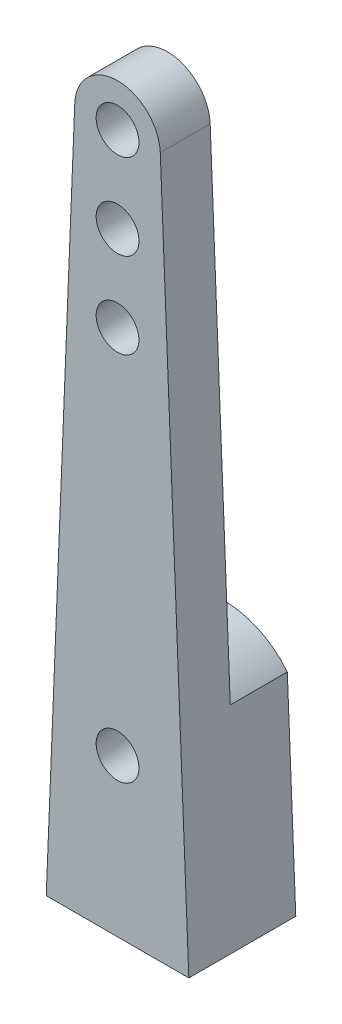
SolidWorks part; units mm, degrees
ref_plane "前视基准面" through (0, 0, 0) normal (0, 0, 1) x (1, 0, 0)
ref_plane "上视基准面" through (0, 0, 0) normal (0, 1, 0) x (1, 0, 0)
ref_plane "右视基准面" through (0, 0, 0) normal (1, 0, 0) x (0, 0, -1)
sketch "草图1" plane through (0, 0, 0) normal (0, 0, 1) x (1, 0, 0)
  line L0 (-5, 0) -> (5, 0)
  line L1 (-2.9975, 49.1222) -> (-5, 0)
  line L2 (0, 23.7926) -> (0, -9.9245) construction
  line L3 (2.9975, 49.1222) -> (5, 0)
  arc A0 (2.9975, 49.1222) -> (-2.9975, 49.1222) centre (0, 49) ccw
  circle A1 centre (0, 49) radius 1.5
  circle A2 centre (0, 43) radius 1.5
  circle A3 centre (0, 37) radius 1.5
  circle A4 centre (0, 11) radius 2.75
  point P1 (0, 52)
  point P9 (0, 0)
  dimension "D1" = 10
  dimension "D2" = 3
  dimension "D4" = 3
  dimension "D5" = 5.5
  dimension "D6" = 38
  dimension "D7" = 32
  dimension "D8" = 26
  dimension "D9" = 3
  dimension "D10" = 3
  dimension "D3" = 52
extrude "凸台-拉伸1" add sketch "草图1" along normal blind 3.5
sketch "草图2" plane through (0, 0, 0) normal (0, 0, -1) x (-1, 0, 0)
  line L3 (5, 0) -> (2.9975, 49.1222)
  line L4 (-2.9975, 49.1222) -> (-5, 0)
  line L5 (-5, 0) -> (5, 0)
  line L6 (5, 0) -> (4.4072, 14.541)
  line L7 (-4.4072, 14.541) -> (-5, 0)
  line L8 (-5, 0) -> (5, 0)
  arc A0 (4.4072, 14.541) -> (-4.4072, 14.541) centre (0, 11) ccw
  arc A1 (2.9975, 49.1222) -> (-2.9975, 49.1222) centre (0, 49) ccw
  dimension "D1" = 0
extrude "凸台-拉伸2" add sketch "草图2" along normal blind 4
sketch "草图4" plane through (0, 0, 3.5) normal (0, 0, 1) x (1, 0, 0)
  circle A1 centre (0, 11) radius 2.75
  circle A2 centre (0, 11) radius 2.75
  dimension "D1" = 0
extrude "凸台-拉伸3" add sketch "草图4" against normal blind 5
sketch "草图5" plane through (0, 0, -4) normal (0, 0, -1) x (-1, 0, 0)
  circle A0 centre (0, 11) radius 2.75
  dimension "D1" = 5.5
extrude "切除-拉伸2" cut sketch "草图5" against normal blind 4
sketch "草图6" plane through (0, 0, 0) normal (0, 0, -1) x (-1, 0, 0)
  circle A0 centre (0, 11) radius 1.5
  dimension "D1" = 3
extrude "切除-拉伸3" cut sketch "草图6" against normal blind 4
